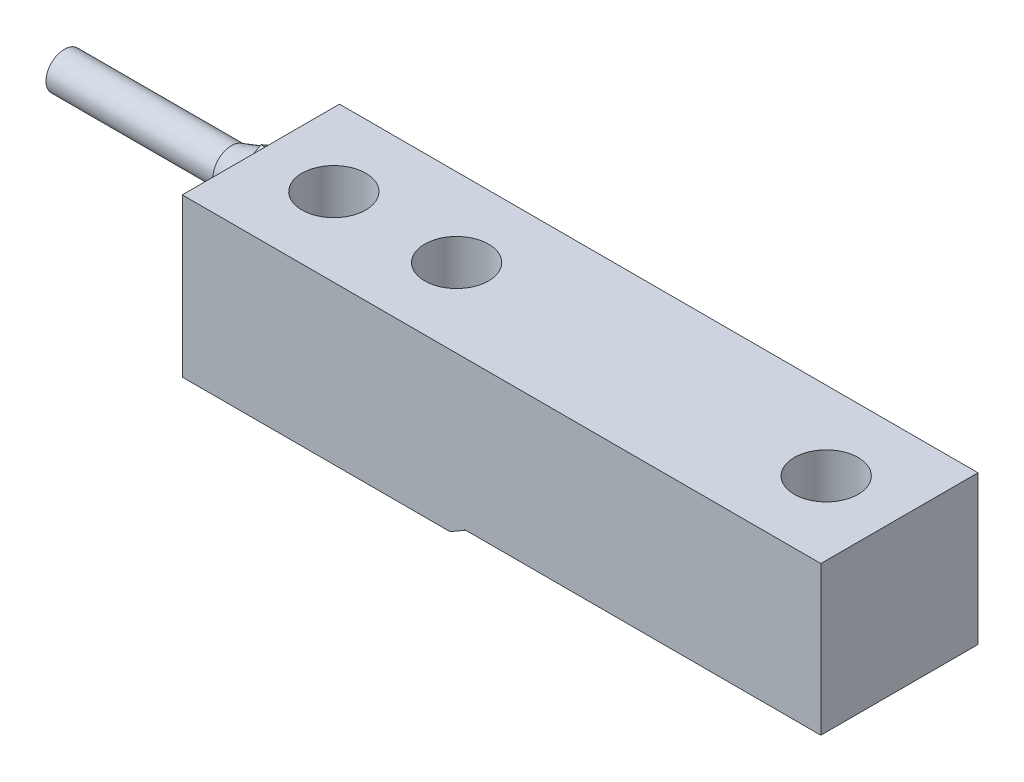
SolidWorks part; units mm, degrees
material "Plain Carbon Steel"
ref_plane "Front Plane" through (0, 0, 0) normal (0, 0, 1) x (1, 0, 0)
ref_plane "Top Plane" through (0, 0, 0) normal (0, 1, 0) x (1, 0, 0)
ref_plane "Right Plane" through (0, 0, 0) normal (1, 0, 0) x (0, 0, -1)
sketch "Sketch1" plane through (0, 0, 0) normal (0, 1, 0) x (1, 0, 0)
  line L1 (0, 0) -> (130, 0)
  line L2 (0, 0) -> (0, 32)
  line L3 (0, 32) -> (130, 32)
  line L4 (130, 0) -> (130, 32)
  line L5 (0, 0) -> (130, 32) construction
  line L6 (0, 32) -> (130, 0) construction
  point P4 (65, 16)
  dimension "D1" = 130
  dimension "D2" = 32
extrude "Boss-Extrude1" add sketch "Sketch1" along normal blind 32.131
sketch "Sketch2" plane through (0, 32.131, 0) normal (0, 1, 0) x (1, 0, 0)
  line L0 (0, 16) -> (14.85, 16) construction
  line L1 (0, 32) -> (0, 0) construction
  line L2 (14.85, 16) -> (39.85, 16) construction
  circle A0 centre (14.85, 16) radius 6.5
  circle A1 centre (39.85, 16) radius 6.5
  point P7 (8.35, 16)
  point P10 (46.35, 16)
  dimension "D1" = 25
  dimension "D2" = 13
  dimension "D3" = 8.35
extrude "Cut-Extrude1" cut sketch "Sketch2" against normal through all
sketch "Sketch3" plane through (0, 32.131, 0) normal (0, 1, 0) x (1, 0, 0)
  line L0 (108.6, 16) -> (46.35, 16) construction
  line L1 (115.1, 16) -> (115.1, 0) construction
  line L2 (0, 0) -> (130, 0) construction
  line L3 (115.1, 16) -> (115.1, 32) construction
  line L4 (130, 32) -> (0, 32) construction
  circle A0 centre (115.1, 16) radius 6.5
  circle A1 centre (39.85, 16) radius 6.5 construction
  dimension "D1" = 62.25
extrude "Cut-Extrude2" cut sketch "Sketch3" against normal blind 12
sketch "Sketch7" plane through (0, 20.131, 0) normal (0, 1, 0) x (1, 0, 0)
  point P0 (115.1, 16)
hole_wizard "Tap Drill for M12x1.75 Tap1" positions "Sketch8" profile "Sketch9" hole size "M12x1.75" standard "ANSI Metric" end condition through all
sketch "Sketch8" plane through (0, 20.131, 0) normal (0, 1, 0) x (1, 0, 0)
  point P0 (115.1, 16)
sketch "Sketch9" plane through (115.1, 20.131, -16) normal (1, 0, 0) x (0, 0, 1)
  line L0 (0, 0) -> (0, 20.131)
  line L1 (0, 20.131) -> (5.1, 20.131)
  line L2 (5.1, 20.131) -> (5.1, 0)
  line L5 (5.1, 0) -> (0, 0)
  line L11 (0, -6.35) -> (0, 107.95) construction
  dimension "Thru Hole Dia." = 10.2
  dimension "Thru Hole Depth" = 20.131
sketch "Sketch10" plane through (0, 32.131, 0) normal (0, 1, 0) x (1, 0, 0)
  line L0 (0, 0) -> (130, 0) construction
  line L1 (130, 32) -> (57.5, 32)
  line L2 (130, 32) -> (130, 0)
  line L3 (130, 0) -> (57.5, 0)
  line L4 (57.5, 32) -> (57.5, 0)
  line L5 (130, 32) -> (57.5, 0) construction
  line L6 (130, 0) -> (57.5, 32) construction
  point P4 (93.75, 16)
  dimension "D1" = 72.5
extrude "Cut-Extrude3" cut sketch "Sketch10" along normal blind 1.85 from surface at -32.131 starting at face at (115.1, 0, -10.9)
chamfer "Chamfer1" distance 3 angle 30 1 edges at (57.5, 0, -16)
sketch "Sketch12" plane through (0, 0, 0) normal (-1, 0, 0) x (0, 0, 1)
  line L0 (-26, 16.0655) -> (-26, 32.131) construction
  line L1 (-20, 12.6014) -> (-20, 19.5296)
  line L2 (-20, 19.5296) -> (-26, 22.9937)
  line L3 (-26, 22.9937) -> (-32, 19.5296)
  line L4 (-32, 19.5296) -> (-32, 12.6014)
  line L5 (-32, 12.6014) -> (-26, 9.1373)
  line L6 (-26, 9.1373) -> (-20, 12.6014)
  line L7 (-32, 32.131) -> (0, 32.131) construction
  line L8 (-26, 16.0655) -> (-26, 0) construction
  line L9 (-32, 0) -> (0, 0) construction
  line L11 (-32, 32.131) -> (-32, 0) construction
  circle A0 centre (-26, 16.0655) radius 6 construction
  dimension "D1" = 12
extrude "Boss-Extrude2" add sketch "Sketch12" along normal blind 10
ref_plane "Plane2" through (0, 0, -26) normal (0, 0, 1) x (1, 0, 0)
sketch "Sketch13" plane through (0, 0, -26) normal (0, 0, 1) x (1, 0, 0)
  line L0 (-10, 22.9937) -> (0, 22.9937) construction
  line L1 (-1, 22.9937) -> (0, 22.9937)
  line L2 (-1, 22.9937) -> (-1, 21.9937)
  line L3 (-1, 21.9937) -> (0, 21.9937)
  line L4 (0, 22.9937) -> (0, 21.9937)
  line L5 (-1, 22.9937) -> (0, 21.9937) construction
  line L6 (-1, 21.9937) -> (0, 22.9937) construction
  line L8 (0, 16.0655) -> (-10, 16.0655) construction
  line L9 (0, 32.131) -> (0, 0) construction
  line L10 (-10, 12.6014) -> (-10, 19.5296) construction
  line L11 (-10, 21.2617) -> (-6, 21.2617) construction
  line L12 (-6, 22.9937) -> (-5, 22.9937)
  line L13 (-6, 22.9937) -> (-6, 21.9937)
  line L14 (-6, 21.9937) -> (-5, 21.9937)
  line L15 (-5, 22.9937) -> (-5, 21.9937)
  line L16 (-6, 22.9937) -> (-5, 21.9937) construction
  line L17 (-6, 21.9937) -> (-5, 22.9937) construction
  line L18 (-10, 19.5296) -> (-10, 22.9937) construction
  line L19 (-5, 21.2617) -> (-1, 21.2617) construction
  line L20 (-6, 21.2617) -> (-6, 21.9937) construction
  line L21 (-5, 21.9937) -> (-5, 21.2617) construction
  line L22 (-1, 21.2617) -> (-1, 21.9937) construction
  point P4 (-0.5, 22.4937)
  point P17 (-5.5, 22.4937)
  dimension "D1" = 1
  dimension "D2" = 1
revolve "Cut-Revolve1" cut sketch "Sketch13" angle 360 about L8
sketch "Sketch14" plane through (0, 0, -26) normal (0, 0, 1) x (1, 0, 0)
  line L0 (-10, 21.8155) -> (-16, 19.8155)
  line L1 (-10, 19.5296) -> (-10, 22.9937) construction
  line L2 (-16, 19.8155) -> (-50, 19.8155)
  line L3 (-50, 19.8155) -> (-50, 16.0655)
  line L4 (-50, 16.0655) -> (-10, 16.0655) construction
  line L5 (-10, 12.6014) -> (-10, 19.5296) construction
  line L6 (0, 21.9937) -> (0, 10.1373) construction
  line L7 (-10, 21.8155) -> (-10, 16.0655)
  line L8 (-50, 16.0655) -> (-10, 16.0655)
  point P11 (-10, 21.2617)
  dimension "D1" = 50
  dimension "D2" = 6
  dimension "D3" = 5.75
  dimension "D4" = 3.75
revolve "Revolve2" add sketch "Sketch14" angle 360 about L4
